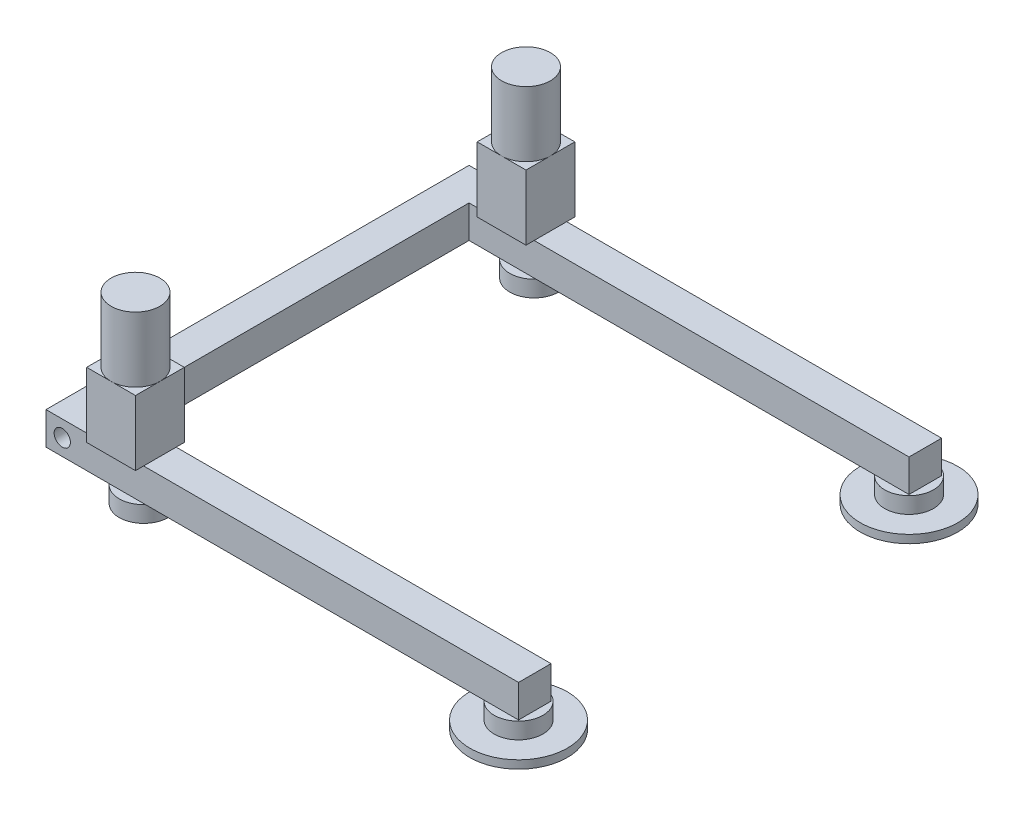
SolidWorks part; units mm, degrees
ref_plane "Front Plane" through (0, 0, 0) normal (0, 0, 1) x (1, 0, 0)
ref_plane "Top Plane" through (0, 0, 0) normal (0, 1, 0) x (1, 0, 0)
ref_plane "Right Plane" through (0, 0, 0) normal (1, 0, 0) x (0, 0, -1)
sketch "Sketch1" plane through (0, 0, 0) normal (0, 1, 0) x (1, 0, 0)
  line L0 (0, 0) -> (0, 166.346)
  line L1 (0, 166.346) -> (368.8272, 166.346)
  line L2 (368.8272, 166.346) -> (368.8272, 140.946)
  line L3 (368.8272, 140.946) -> (25.4, 140.946)
  line L4 (25.4, 140.946) -> (25.4, -138.454)
  line L5 (25.4, -138.454) -> (368.8272, -138.454)
  line L6 (368.8272, -138.454) -> (368.8272, -163.854)
  line L7 (368.8272, -163.854) -> (0, -163.854)
  line L8 (0, -163.854) -> (0, 0)
  dimension "D1" = 330.2
  dimension "D2" = 25.4
  dimension "D3" = 25.4
  dimension "D4" = 25.4
extrude "Boss-Extrude1" add sketch "Sketch1" along normal blind 25.4
sketch "Sketch3" plane through (0, 25.4, 0) normal (0, 1, 0) x (1, 0, 0)
  line L1 (38.1, -132.104) -> (76.2, -132.104)
  line L2 (38.1, -132.104) -> (38.1, -170.204)
  line L3 (38.1, -170.204) -> (76.2, -170.204)
  line L4 (76.2, -132.104) -> (76.2, -170.204)
  line L5 (0, -163.854) -> (368.8272, -163.854) construction
  line L6 (25.4, -138.454) -> (25.4, 140.946) construction
  point P8 (38.1, -151.154)
  dimension "D1" = 38.1
  dimension "D2" = 38.1
  dimension "D3" = 12.7
  dimension "D4" = 12.7
extrude "Boss-Extrude2" add sketch "Sketch3" along normal blind 50.8 contours L4 L3 L2 L1
sketch "Sketch4" plane through (0, 76.2, 0) normal (0, 1, 0) x (1, 0, 0)
  line L0 (38.1, -132.104) -> (38.1, -170.204) construction
  line L1 (38.1, -132.104) -> (76.2, -132.104) construction
  circle A0 centre (57.15, -151.154) radius 19.05
  point P2 (0, 0)
  point P5 (38.1, -151.154)
  point P6 (57.006, -151.154)
  point P7 (57.4231, -151.154)
  point P8 (55.0635, -151.154)
  point P9 (0, 0)
  point P10 (0, 0)
  point P11 (0, 0)
  point P12 (57.15, -169.3716)
  point P15 (57.15, -132.104)
  dimension "D1" = 38.1
extrude "Boss-Extrude3" add sketch "Sketch4" along normal blind 50.8
pattern_linear "LPattern1" count 2 spacing 304.8 along (0, 0, -1) of "Boss-Extrude2", "Boss-Extrude3"
sketch "Sketch5" plane through (0, 0, 0) normal (0, -1, 0) x (1, 0, 0)
  line L0 (0, -166.346) -> (0, 163.854) construction
  line L1 (0, 163.854) -> (368.8272, 163.854) construction
  circle A0 centre (63.5, 151.154) radius 19.05
  point P2 (0, 0)
  dimension "D1" = 38.1
  dimension "D2" = 63.5
  dimension "D3" = 12.7
extrude "Boss-Extrude4" add sketch "Sketch5" along normal blind 12.7
sketch "Sketch6" plane through (0, -12.7, 0) normal (0, -1, 0) x (1, 0, 0)
  circle A0 centre (63.5, 151.154) radius 6.35
  circle A1 centre (63.5, 151.154) radius 19.05 construction
  dimension "D1" = 12.7
extrude "Boss-Extrude5" add sketch "Sketch6" along normal blind 6.35
pattern_linear "LPattern2" count 2 spacing 304.8 along (0, 0, -1) of "Boss-Extrude4", "Boss-Extrude5"
sketch "Sketch7" plane through (0, 0, 0) normal (0, -1, 0) x (1, 0, 0)
  line L0 (368.8272, 163.854) -> (368.8272, 138.454) construction
  circle A0 centre (356.1272, 151.154) radius 19.05
  point P2 (0, 0)
  point P5 (368.8272, 151.154)
  point P6 (0, 0)
  dimension "D1" = 38.1
  dimension "D2" = 12.7
extrude "Boss-Extrude6" add sketch "Sketch7" along normal blind 12.7
sketch "Sketch8" plane through (0, -12.7, 0) normal (0, -1, 0) x (1, 0, 0)
  circle A0 centre (356.1272, 151.154) radius 38.1
  circle A1 centre (356.1272, 151.154) radius 19.05 construction
  dimension "D1" = 76.2
extrude "Boss-Extrude7" add sketch "Sketch8" along normal blind 6.35
pattern_linear "LPattern3" count 2 spacing 304.8 along (0, 0, -1) of "Boss-Extrude6", "Boss-Extrude7"
sketch "Sketch9" plane through (0, 0, 163.854) normal (0, 0, 1) x (1, 0, 0)
  line L0 (0, 25.4) -> (0, 0) construction
  circle A0 centre (12.7, 12.7) radius 6.35
  point P2 (0, 0)
  point P5 (0, 12.7)
  dimension "D1" = 12.7
  dimension "D2" = 12.7
extrude "Cut-Extrude1" cut sketch "Sketch9" along normal through all both and the other way through all
